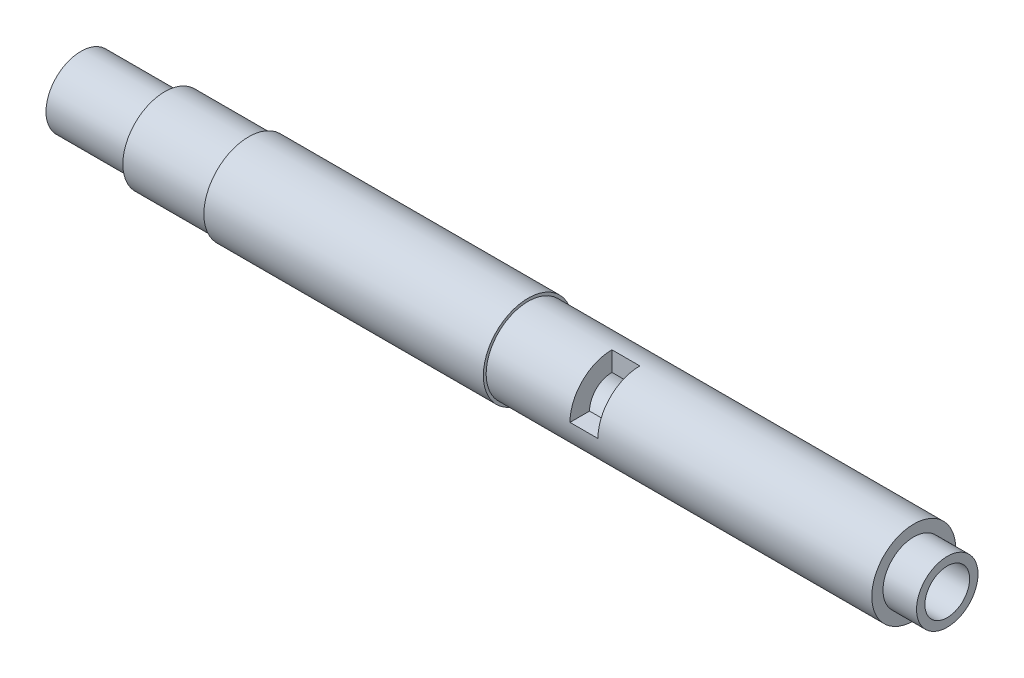
SolidWorks part; units mm, degrees
ref_plane "前视基准面" through (0, 0, 0) normal (0, 0, 1) x (1, 0, 0)
ref_plane "上视基准面" through (0, 0, 0) normal (0, 1, 0) x (1, 0, 0)
ref_plane "右视基准面" through (0, 0, 0) normal (1, 0, 0) x (0, 0, -1)
sketch "草图1" plane through (0, 0, 0) normal (1, 0, 0) x (0, 0, -1)
  circle A0 centre (0, 0) radius 16
extrude "凸台-拉伸1" add sketch "草图1" along normal blind 100
sketch "草图2" plane through (100, 0, 0) normal (1, 0, 0) x (0, 0, -1)
  circle A0 centre (0, 0) radius 16
extrude "凸台-拉伸2" add sketch "草图2" against normal blind 18
sketch "草图3" plane through (100, 0, 0) normal (1, 0, 0) x (0, 0, -1)
  circle A0 centre (0, 0) radius 16
extrude "凸台-拉伸3" add sketch "草图3" along normal blind 132
sketch "草图4" plane through (232, 0, 0) normal (1, 0, 0) x (0, 0, -1)
  circle A0 centre (0, 0) radius 16
extrude "凸台-拉伸4" add sketch "草图4" along normal blind 18
sketch "草图5" plane through (250, 0, 0) normal (1, 0, 0) x (0, 0, -1)
  circle A0 centre (0, 0) radius 16
extrude "凸台-拉伸5" add sketch "草图5" along normal blind 50
sketch "草图6" plane through (300, 0, 0) normal (1, 0, 0) x (0, 0, -1)
  circle A0 centre (0, 0) radius 16
extrude "凸台-拉伸6" add sketch "草图6" along normal blind 80
sketch "草图7" plane through (380, 0, 0) normal (1, 0, 0) x (0, 0, -1)
  circle A0 centre (0, 0) radius 16
extrude "凸台-拉伸7" add sketch "草图7" along normal blind 50
sketch "草图9" plane through (430, 0, 0) normal (1, 0, 0) x (0, 0, -1)
  circle A0 centre (0, 0) radius 8
extrude "凸台-拉伸8" add sketch "草图9" along normal blind 20
sketch "草图13" plane through (0, 0, 0) normal (-1, 0, 0) x (0, 0, 1)
  circle A0 centre (0, 0) radius 8
extrude "切除-拉伸5" cut sketch "草图13" against normal up to surface (450 mm away) up to face at (450, 0, -8)
sketch "草图14" plane through (0, 0, 0) normal (-1, 0, 0) x (0, 0, 1)
  circle A0 centre (0, 0) radius 12.5
  circle A1 centre (0, 0) radius 16
extrude "切除-拉伸6" cut sketch "草图14" against normal blind 30
sketch "草图16" plane through (30, 0, 0) normal (-1, 0, 0) x (0, 0, 1)
  circle A0 centre (0, 0) radius 15
  circle A1 centre (0, 0) radius 16
extrude "切除-拉伸8" cut sketch "草图16" against normal blind 30
ref_plane "基准面1" through (160, 0, 0) normal (-1, 0, 0) x (0, 0, 1)
sketch "草图17" plane through (160, 0, 0) normal (-1, 0, 0) x (0, 0, 1)
  circle A0 centre (0, 0) radius 15
  circle A1 centre (0, 0) radius 16
extrude "切除-拉伸9" cut sketch "草图17" against normal blind 60
sketch "草图18" plane through (430, 0, 0) normal (1, 0, 0) x (0, 0, -1)
  circle A0 centre (0, 0) radius 16
extrude "切除-拉伸10" cut sketch "草图18" against normal blind 200
sketch "草图19" plane through (230, 0, 0) normal (1, 0, 0) x (0, 0, -1)
  circle A2 centre (0, 0) radius 16
  circle A4 centre (0, 0) radius 8
extrude "切除-拉伸11" cut sketch "草图19" against normal blind 20
sketch "草图20" plane through (210, 0, 0) normal (1, 0, 0) x (0, 0, -1)
  circle A0 centre (0, 0) radius 8
  circle A1 centre (0, 0) radius 15
extrude "凸台-拉伸9" add sketch "草图20" along normal blind 100
ref_plane "基准面2" through (200, 0, 0) normal (1, 0, 0) x (0, 0, -1)
sketch "草图21" plane through (200, 0, 0) normal (1, 0, 0) x (0, 0, -1)
  line L0 (-15, 0) -> (-8, 0)
  line L1 (0, 0) -> (0, 18.4597) construction
  line L2 (0, 18.4597) -> (0, -20.4002) construction
  line L3 (0, 15) -> (0, 8)
  line L4 (8, 0) -> (15, 0)
  line L5 (0, -8) -> (0, -15)
  arc A1 (-15, 0) -> (0, 15) centre (0, 0) cw
  circle A2 centre (0, 0) radius 15 construction
  arc A3 (15, 0) -> (0, -15) centre (0, 0) cw
  arc A4 (-8, 0) -> (0, 8) centre (0, 0) cw
  circle A5 centre (0, 0) radius 8 construction
  arc A6 (8, 0) -> (0, -8) centre (0, 0) cw
extrude "切除-拉伸12" cut sketch "草图21" against normal blind 10
sketch "草图22" plane through (310, 0, 0) normal (1, 0, 0) x (0, 0, -1)
  circle A0 centre (0, 0) radius 15
  circle A1 centre (0, 0) radius 11
extrude "切除-拉伸13" cut sketch "草图22" against normal blind 12
